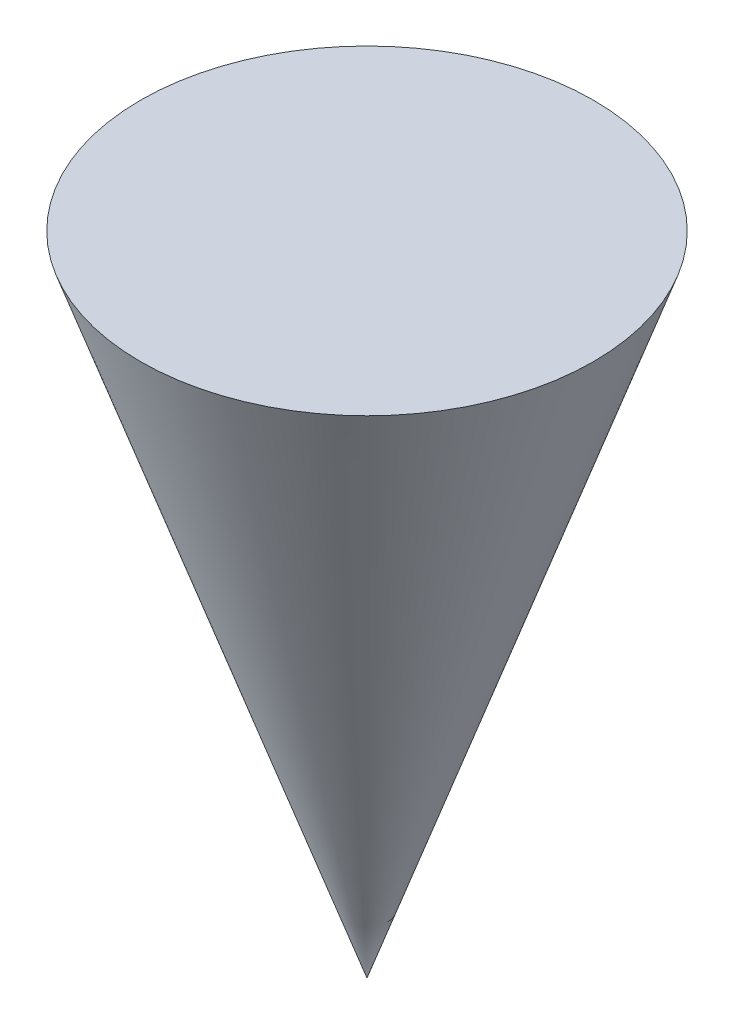
SolidWorks part; units mm, degrees
ref_plane "Front Plane" through (0, 0, 0) normal (0, 0, 1) x (1, 0, 0)
ref_plane "Top Plane" through (0, 0, 0) normal (0, 1, 0) x (1, 0, 0)
ref_plane "Right Plane" through (0, 0, 0) normal (1, 0, 0) x (0, 0, -1)
sketch "Sketch1" plane through (0, 0, 0) normal (0, 0, 1) x (1, 0, 0)
  line L0 (0, 0) -> (0, 20)
  line L1 (0, 20) -> (7, 20)
  line L2 (7, 20) -> (0, 0)
  dimension "D1" = 7
  dimension "D2" = 20
revolve "Revolve1" add sketch "Sketch1" angle 360 about L0
